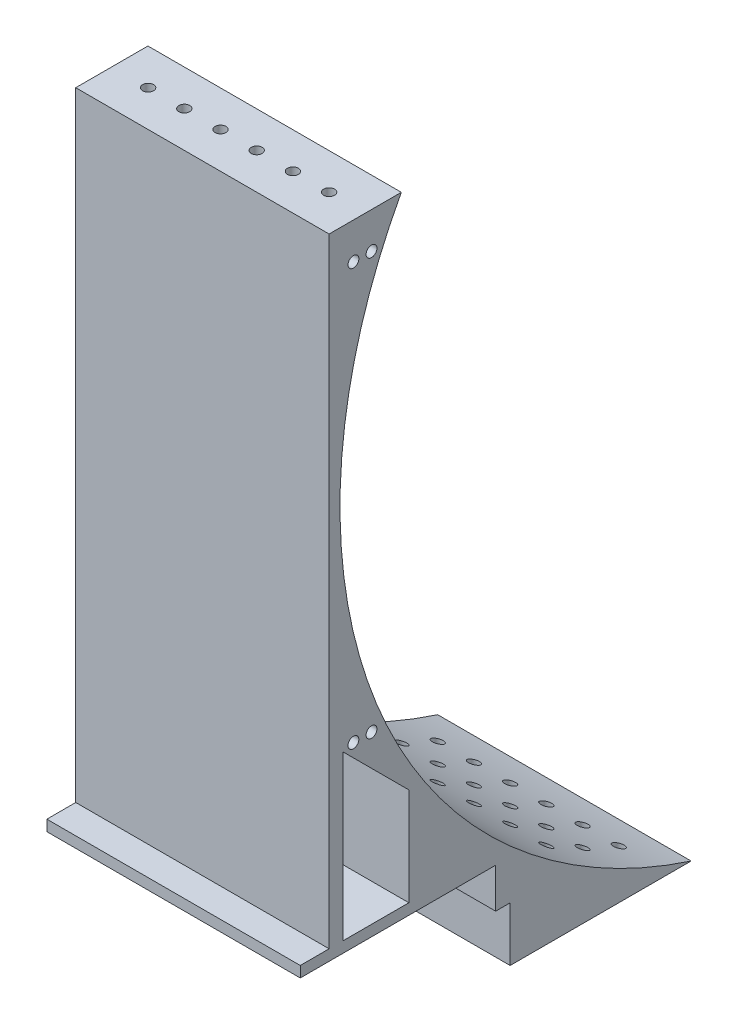
SolidWorks part; units mm, degrees
ref_plane "Front Plane" through (0, 0, 0) normal (0, 0, 1) x (1, 0, 0)
ref_plane "Top Plane" through (0, 0, 0) normal (0, 1, 0) x (1, 0, 0)
ref_plane "Right Plane" through (0, 0, 0) normal (1, 0, 0) x (0, 0, -1)
sketch "Sketch1" plane through (0, 0, 0) normal (1, 0, 0) x (0, 0, -1)
  line L0 (0, 200) -> (0, 0)
  line L1 (0, 0) -> (100, 0)
  line L2 (0, 200) -> (19.9466, 200)
  arc A0 (19.9466, 200) -> (100, 0) centre (143, 133.2329) ccw
  point P6 (140.3465, 119.5965)
  point P7 (117.7027, 2.4511)
  point P8 (142.4139, 127.4391)
  point P9 (141.3016, 129.9036)
  point P10 (55.5523, 211.4955)
  point P11 (104.3656, 88.9803)
  point P12 (0, 0)
  dimension "D1" = 140
  dimension "D4" = 143
  dimension "D2" = 200
extrude "Boss-Extrude1" add sketch "Sketch1" along normal blind 70
ref_plane "Plane1" through (0, 0, -100) normal (0, 0, 1) x (1, 0, 0)
sketch "Sketch5" plane through (70, 0, 0) normal (1, 0, 0) x (0, 0, -1)
  line L0 (22.0273, 26) -> (22.0273, 56)
  line L1 (0, 0) -> (50, 0)
  line L3 (22.0273, 26) -> (46, 26)
  line L4 (50, 0) -> (50, 15)
  line L5 (22.0273, 56) -> (3.8589, 74.1684)
  line L7 (0, 26) -> (0, 0)
  line L8 (3.8589, 74.1684) -> (3.8589, 26)
  line L11 (50, 15) -> (46, 15)
  line L12 (46, 26) -> (46, 15)
  line L13 (3.8589, 26) -> (0, 26)
  dimension "D1" = 135
  dimension "D2" = 50
  dimension "D3" = 15
  dimension "D4" = 30
  dimension "D5" = 4
  dimension "D6" = 11
extrude "Cut-Extrude2" cut sketch "Sketch5" against normal through all
sketch "Sketch6" plane through (0, 0, -22.0273) normal (0, 0, 1) x (1, 0, 0)
  line L0 (70, 26) -> (70, 56) construction
  line L1 (0, 26) -> (70, 26)
  line L2 (0, 26) -> (0, 29)
  line L3 (0, 29) -> (70, 29)
  line L4 (70, 26) -> (70, 29)
  dimension "D1" = 3
extrude "Boss-Extrude2" add sketch "Sketch6" along normal blind 30
sketch "Sketch7" plane through (0, 200, 0) normal (0, 1, 0) x (1, 0, 0)
  line L1 (0, 19.9466) -> (0, 0) construction
  line L2 (70, 0) -> (0, 0) construction
  circle A0 centre (10, 10) radius 1.5
  circle A1 centre (20, 10) radius 1.5
  circle A2 centre (30, 10) radius 1.5
  circle A3 centre (40, 10) radius 1.5
  circle A4 centre (50, 10) radius 1.5
  circle A5 centre (60, 10) radius 1.5
  dimension "D2" = 3
  dimension "D3" = 10
  dimension "D1" = 10
  dimension "D4" = 6
extrude "Cut-Extrude3" cut sketch "Sketch7" against normal blind 20
sketch "Sketch8" plane through (0, 0, 0) normal (0, -1, 0) x (1, 0, 0)
  line L0 (70, -100) -> (0, -100) construction
  line L1 (0, -50) -> (0, -100) construction
  circle A0 centre (10, -90) radius 1.5
  circle A1 centre (20, -90) radius 1.5
  circle A2 centre (30, -90) radius 1.5
  circle A3 centre (40, -90) radius 1.5
  circle A4 centre (50, -90) radius 1.5
  circle A5 centre (60, -90) radius 1.5
  circle A6 centre (20, -80) radius 1.5
  circle A7 centre (30, -80) radius 1.5
  circle A8 centre (40, -80) radius 1.5
  circle A9 centre (50, -80) radius 1.5
  circle A10 centre (60, -80) radius 1.5
  circle A11 centre (20, -70) radius 1.5
  circle A12 centre (30, -70) radius 1.5
  circle A13 centre (40, -70) radius 1.5
  circle A14 centre (50, -70) radius 1.5
  circle A15 centre (60, -70) radius 1.5
  circle A16 centre (20, -60) radius 1.5
  circle A17 centre (30, -60) radius 1.5
  circle A18 centre (40, -60) radius 1.5
  circle A19 centre (50, -60) radius 1.5
  circle A20 centre (60, -60) radius 1.5
  circle A21 centre (10, -80) radius 1.5
  circle A22 centre (10, -70) radius 1.5
  circle A23 centre (10, -60) radius 1.5
  dimension "D1" = 3
  dimension "D2" = 10
  dimension "D3" = 10
  dimension "D4" = 6
  dimension "D5" = 4
extrude "Cut-Extrude4" cut sketch "Sketch8" against normal blind 15
sketch "Sketch9" plane through (0, 26, 0) normal (0, -1, 0) x (1, 0, 0)
  line L0 (35, 7.9727) -> (35, -46) construction
  line L1 (0, 7.9727) -> (70, 7.9727) construction
  line L2 (0, -46) -> (70, -46) construction
  line L3 (0, -46) -> (70, -46) construction
  circle A0 centre (20, -6) radius 1.5
  circle A1 centre (20, -31) radius 1.5
  circle A2 centre (50, -31) radius 1.5
  circle A3 centre (50, -6) radius 1.5
  dimension "D1" = 3
  dimension "D2" = 3
  dimension "D3" = 25
  dimension "D4" = 15
  dimension "D5" = 15
extrude "Cut-Extrude5" cut sketch "Sketch9" against normal blind 20
sketch "Sketch10" plane through (70, 0, 0) normal (1, 0, 0) x (0, 0, -1)
  line L0 (46, 26) -> (-7.9727, 26) construction
  line L1 (0, 200) -> (0, 29) construction
  circle A0 centre (6.71, 75) radius 1.5
  circle A2 centre (11.71, 75) radius 1.5
  circle A3 centre (6.71, 190) radius 1.5
  circle A4 centre (11.71, 190) radius 1.5
  dimension "D2" = 3
  dimension "D3" = 6.71
  dimension "D1" = 49
  dimension "D4" = 2
  dimension "D5" = 2
extrude "Cut-Extrude6" cut sketch "Sketch10" against normal through all
